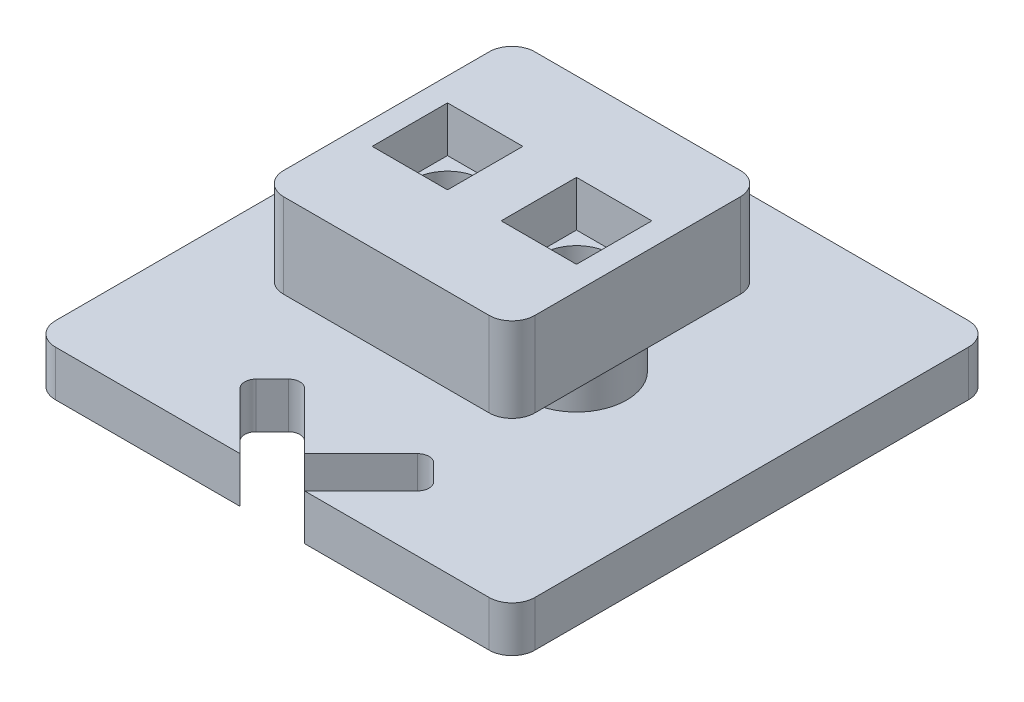
SolidWorks part; units mm, degrees
ref_plane "Front Plane" through (0, 0, 0) normal (0, 0, 1) x (1, 0, 0)
ref_plane "Top Plane" through (0, 0, 0) normal (0, 1, 0) x (1, 0, 0)
ref_plane "Right Plane" through (0, 0, 0) normal (1, 0, 0) x (0, 0, -1)
sketch "Sketch1" plane through (0, 0, 0) normal (0, 1, 0) x (1, 0, 0)
  line L1 (-5.5, -5.5) -> (5.5, -5.5)
  line L2 (-5.5, -5.5) -> (-5.5, 5.5)
  line L3 (-5.5, 5.5) -> (5.5, 5.5)
  line L4 (5.5, -5.5) -> (5.5, 5.5)
  line L5 (-5.5, -5.5) -> (5.5, 5.5) construction
  line L6 (-5.5, 5.5) -> (5.5, -5.5) construction
  point P0 (0, 0)
  dimension "D1" = 11
  dimension "D2" = 11
extrude "Boss-Extrude1" add sketch "Sketch1" along normal blind 3.7
fillet "Fillet1" radius 1 4 edges at (-5.5, 1.85, -5.5) (-5.5, 1.85, 5.5) (5.5, 1.85, -5.5) (5.5, 1.85, 5.5)
sketch "Sketch2" plane through (0, 3.7, 0) normal (0, 1, 0) x (1, 0, 0)
  line L0 (-2.825, 0) -> (2.825, 0) construction
  line L2 (-4.475, -1.65) -> (-1.175, -1.65)
  line L3 (-4.475, -1.65) -> (-4.475, 1.65)
  line L4 (-4.475, 1.65) -> (-1.175, 1.65)
  line L5 (-1.175, -1.65) -> (-1.175, 1.65)
  line L6 (-4.475, -1.65) -> (-1.175, 1.65) construction
  line L7 (-4.475, 1.65) -> (-1.175, -1.65) construction
  line L8 (1.175, -1.65) -> (4.475, -1.65)
  line L9 (1.175, -1.65) -> (1.175, 1.65)
  line L10 (1.175, 1.65) -> (4.475, 1.65)
  line L11 (4.475, -1.65) -> (4.475, 1.65)
  line L12 (1.175, -1.65) -> (4.475, 1.65) construction
  line L13 (1.175, 1.65) -> (4.475, -1.65) construction
  point P4 (0, 0)
  dimension "D1" = 3.3
  dimension "D2" = 3.3
  dimension "D3" = 3.3
  dimension "D4" = 3.3
  dimension "D5" = 5.65
extrude "Cut-Extrude1" cut sketch "Sketch2" against normal blind 2
sketch "Sketch4" plane through (0, 0, 0) normal (0, -1, 0) x (-1, 0, 0)
  line L0 (2.825, 0) -> (-2.825, 0) construction
  circle A0 centre (2.825, 0) radius 2.2
  circle A1 centre (-2.825, 0) radius 2.2
  point P4 (0, 0)
  point P8 (0, 0)
  dimension "D1" = 5.65
  dimension "D2" = 4.4
  dimension "D3" = 4.4
extrude "Boss-Extrude2" add sketch "Sketch4" along normal blind 4
sketch "Sketch5" plane through (0, -4, 0) normal (0, -1, 0) x (-1, 0, 0)
  line L1 (9.5, 10.5) -> (-9.5, 10.5)
  line L2 (10.5, 9.5) -> (10.5, -9.5)
  line L3 (9.5, -10.5) -> (-9.5, -10.5)
  line L4 (-10.5, 9.5) -> (-10.5, -9.5)
  line L5 (10.5, 10.5) -> (-10.5, -10.5) construction
  line L6 (10.5, -10.5) -> (-10.5, 10.5) construction
  arc A0 (10.5, -9.5) -> (9.5, -10.5) centre (9.5, -9.5) cw
  arc A1 (-10.5, -9.5) -> (-9.5, -10.5) centre (-9.5, -9.5) ccw
  arc A2 (-9.5, 10.5) -> (-10.5, 9.5) centre (-9.5, 9.5) ccw
  arc A3 (9.5, 10.5) -> (10.5, 9.5) centre (9.5, 9.5) cw
  point P0 (0, 0)
  dimension "D3" = 1
  dimension "D1" = 21
  dimension "D2" = 21
extrude "Boss-Extrude3" add sketch "Sketch5" against normal blind 2
sketch "Sketch3" plane through (0, 3.7, 0) normal (0, 1, 0) x (1, 0, 0)
  line L0 (-2.825, 0) -> (2.825, 0) construction
  circle A0 centre (-2.825, 0) radius 1.5
  circle A1 centre (2.825, 0) radius 1.5
  point P4 (0, 0)
  point P5 (0, 0)
  point P8 (0, 0)
  dimension "D2" = 3
  dimension "D3" = 3
  dimension "D1" = 5.65
extrude "Cut-Extrude2" cut sketch "Sketch3" against normal through all
sketch "Sketch7" plane through (0, -2, 0) normal (0, 1, 0) x (1, 0, 0)
  line L0 (9.5, -10.5) -> (-9.5, -10.5) construction
  line L1 (2.8284, -14.7426) -> (4.2426, -13.3284)
  line L2 (2.8284, -14.7426) -> (-3.8891, -8.0251)
  line L3 (-3.8891, -7.318) -> (-3.182, -6.6109)
  line L4 (4.2426, -13.3284) -> (-2.4749, -6.6109)
  line L5 (2.8284, -14.7426) -> (-2.8284, -6.2574) construction
  line L6 (-4.2426, -7.6716) -> (4.2426, -13.3284) construction
  line L8 (-4.2426, -13.3284) -> (-2.8284, -14.7426)
  line L9 (-4.2426, -13.3284) -> (2.4749, -6.6109)
  line L10 (3.182, -6.6109) -> (3.8891, -7.318)
  line L11 (-2.8284, -14.7426) -> (3.8891, -8.0251)
  line L12 (-4.2426, -13.3284) -> (4.2426, -7.6716) construction
  line L13 (2.8284, -6.2574) -> (-2.8284, -14.7426) construction
  arc A0 (-2.4749, -6.6109) -> (-3.182, -6.6109) centre (-2.8284, -6.9645) ccw
  arc A1 (3.8891, -7.318) -> (3.8891, -8.0251) centre (3.5355, -7.6716) cw
  arc A2 (3.182, -6.6109) -> (2.4749, -6.6109) centre (2.8284, -6.9645) ccw
  arc A3 (-3.8891, -7.318) -> (-3.8891, -8.0251) centre (-3.5355, -7.6716) ccw
  point P0 (0, -10.5)
  point P7 (0, -10.5)
  point P12 (-1.4142, -10.5)
  point P13 (1.4142, -10.5)
  line M12 (-9.5, -10.5) -> (9.5, -10.5)
  dimension "D7" = 0.5
  dimension "D8" = 0.5
  dimension "D1" = 2
  dimension "D2" = 45
  dimension "D3" = 2
  dimension "D4" = 45
  dimension "D5" = 4
  dimension "D6" = 4
extrude "Cut-Extrude3" cut sketch "Sketch7" against normal through all contours L10 A2 L9 L4 L11 A1 | L3 A3 L2 L9 L4 A0 | L9 L4 M12
equation "\"D2@Sketch2\"=\"D1@Sketch2\""
equation "\"D3@Sketch2\"=\"D1@Sketch2\""
equation "\"D4@Sketch2\"=\"D1@Sketch2\""
equation "\"D2@Sketch1\"=\"D1@Sketch1\""
equation "\"D3@Sketch3\"=\"D2@Sketch3\""
equation "\"D3@Sketch4\"=\"D2@Sketch4\""
equation "\"D2@Sketch5\"=\"D1@Sketch5\""
equation "\"D3@Sketch7\"=\"D1@Sketch7\""
equation "\"D6@Sketch7\"=\"D5@Sketch7\""
